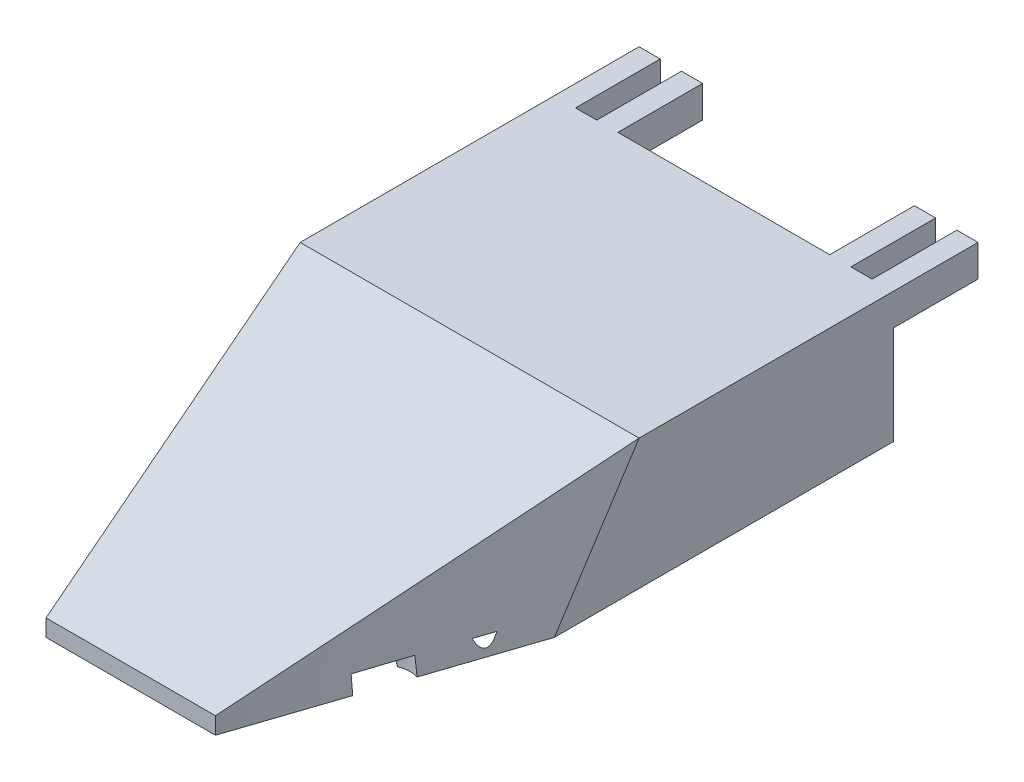
SolidWorks part; units mm, degrees
material "Custom Plastic"
ref_plane "Front Plane" through (0, 0, 0) normal (0, 0, 1) x (1, 0, 0)
ref_plane "Top Plane" through (0, 0, 0) normal (0, 1, 0) x (1, 0, 0)
ref_plane "Right Plane" through (0, 0, 0) normal (1, 0, 0) x (0, 0, -1)
sketch "Sketch4" plane through (0, 0, 0) normal (1, 0, 0) x (0, 0, -1)
  line L0 (0, 0) -> (0, 12.3)
  line L1 (0, 12.3) -> (-24, 12.3)
  line L2 (-24, 12.3) -> (-32, 0)
  line L3 (-32, 0) -> (0, 0)
  dimension "D1" = 24
  dimension "D2" = 32
  dimension "D3" = 12.3
extrude "Boss-Extrude2" add sketch "Sketch4" along normal blind 32
ref_plane "Plane1" through (0, 0, 56) normal (0, 0, 1) x (1, 0, 0)
sketch "Sketch5" plane through (0, 0, 56) normal (0, 0, 1) x (1, 0, 0)
  line L0 (32, 0) -> (0, 0) construction
  line L1 (24, 0) -> (8, 0)
  line L2 (24, 0) -> (24, 1.6)
  line L3 (24, 1.6) -> (8, 1.6)
  line L4 (8, 0) -> (8, 1.6)
  point P6 (16, 0)
  point P7 (16, 0)
  dimension "D1" = 1.6
  dimension "D2" = 16
loft "Loft1" add profiles "Sketch5" section "Sketch5" section face at (16, 6.15, 28)
shell "Shell1" thickness 1.6
sketch "Sketch6" plane through (0, 12.3, 0) normal (0, 1, 0) x (1, 0, 0)
  line L0 (32, 0) -> (0, 0) construction
  line L1 (0, 0) -> (2, 0)
  line L2 (0, 0) -> (0, 8)
  line L3 (0, 8) -> (2, 8)
  line L4 (2, 0) -> (2, 8)
  line L5 (4, 0) -> (6, 0)
  line L6 (4, 0) -> (4, 8)
  line L7 (4, 8) -> (6, 8)
  line L8 (6, 0) -> (6, 8)
  line L10 (32, 0) -> (30, 0)
  line L11 (32, 0) -> (32, 8)
  line L12 (32, 8) -> (30, 8)
  line L13 (30, 0) -> (30, 8)
  line L14 (28, 0) -> (26, 0)
  line L15 (28, 0) -> (28, 8)
  line L16 (28, 8) -> (26, 8)
  line L17 (26, 0) -> (26, 8)
  dimension "D1" = 8
  dimension "D2" = 2
  dimension "D3" = 2
  dimension "D4" = 2
extrude "Boss-Extrude3" add sketch "Sketch6" against normal blind 3
sketch "Sketch8" plane through (0, 0, 0) normal (0, 1, 0) x (1, 0, 0)
  line L0 (8, -56) -> (24, -56) construction
  line L1 (24, -56) -> (24, -48) construction
  line L2 (24, -48) -> (32, -48) construction
  line L3 (32, -48) -> (32, -32) construction
  line L4 (24, -56) -> (32, -32) construction
  line L5 (32, -32) -> (0, -32) construction
  line L6 (0, -32) -> (0, -48) construction
  line L7 (0, -48) -> (8, -48) construction
  line L8 (8, -48) -> (8, -56) construction
  line L9 (24, -48) -> (24, -44) construction
  line L10 (24, -44) -> (28, -44) construction
  line L11 (28, -44) -> (28, -36) construction
  line L12 (-16, -56) -> (0, -56) construction
  circle A0 centre (28, -44) radius 2.4
  circle A1 centre (28, -36) radius 2.4
  circle A2 centre (4, -44) radius 2.4
  circle A3 centre (4, -36) radius 2.4
  dimension "D5" = 4.8
  dimension "D7" = 4.8
  dimension "D1" = 8
  dimension "D2" = 8
  dimension "D3" = 4
  dimension "D4" = 4
  dimension "D6" = 8
  dimension "D9" = 24
  dimension "D8" = 2
extrude "Cut-Extrude2" cut sketch "Sketch8" along normal blind 1.6
